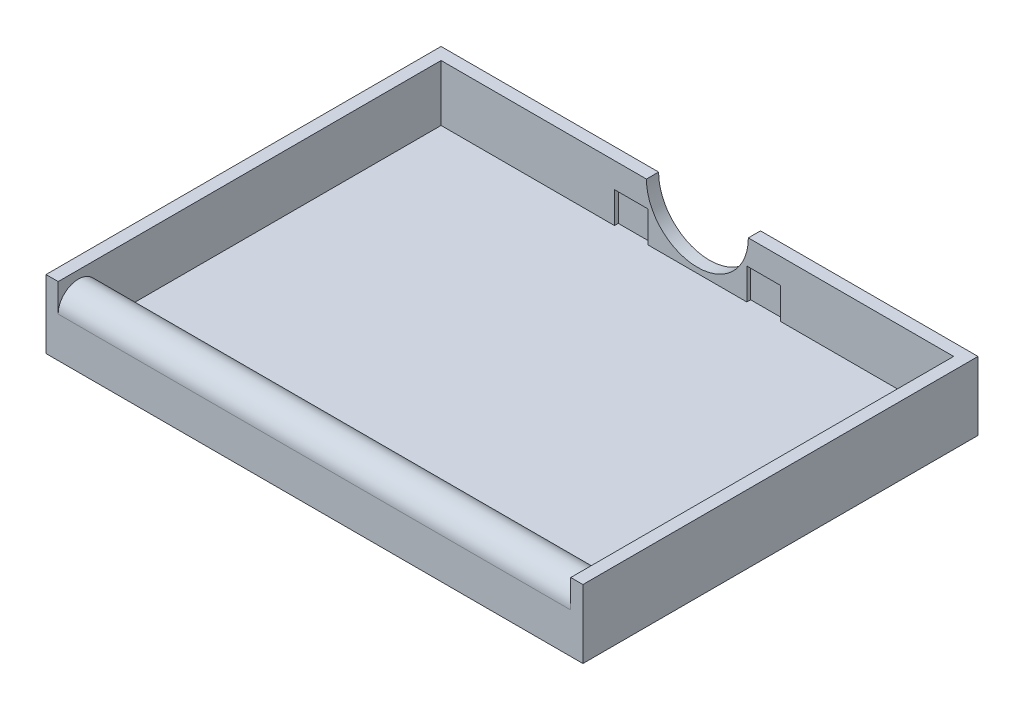
SolidWorks part; units mm, degrees
ref_plane "Front Plane" through (0, 0, 0) normal (0, 0, 1) x (1, 0, 0)
ref_plane "Top Plane" through (0, 0, 0) normal (0, 1, 0) x (1, 0, 0)
ref_plane "Right Plane" through (0, 0, 0) normal (1, 0, 0) x (0, 0, -1)
sketch "Sketch1" plane through (0, 0, 0) normal (0, 1, 0) x (1, 0, 0)
  line L1 (0, 0) -> (70.4, 0)
  line L2 (0, 0) -> (0, -50.7)
  line L3 (0, -50.7) -> (70.4, -50.7)
  line L4 (70.4, 0) -> (70.4, -50.7)
  dimension "D1" = 50.7
  dimension "D2" = 70.4
extrude "Boss-Extrude1" add sketch "Sketch1" along normal blind 1.6
sketch "Sketch2" plane through (0, 1.6, 0) normal (0, 1, 0) x (1, 0, 0)
  line L0 (70.4, -50.7) -> (70.4, 0) construction
  line L1 (0, -50.7) -> (70.4, -50.7)
  line L2 (0, -50.7) -> (0, -48.4)
  line L3 (0, -48.4) -> (70.4, -48.4)
  line L4 (70.4, -50.7) -> (70.4, -48.4)
  dimension "D1" = 2.3
extrude "Boss-Extrude2" add sketch "Sketch2" along normal blind 3.3
sketch "Sketch4" plane through (0, 0, 0) normal (-1, 0, 0) x (0, 0, 1)
  circle A0 centre (48.4, 4.9) radius 2.3
  dimension "D1" = 4.6
extrude "Boss-Extrude3" add sketch "Sketch4" against normal blind 70.4
sketch "Sketch5" plane through (0, 1.6, 0) normal (0, 1, 0) x (1, 0, 0)
  line L0 (70.4, 0) -> (0, 0) construction
  line L1 (1.6, -1.6) -> (68.8, -1.6)
  line L2 (1.6, -1.6) -> (1.6, -50.7)
  line L4 (68.8, -1.6) -> (68.8, -50.7)
  line L5 (0, 0) -> (0, -48.4) construction
  line L6 (70.4, -48.4) -> (70.4, 0) construction
  line L7 (68.8, -50.7) -> (70.4, -50.7)
  line L8 (0, -50.7) -> (1.6, -50.7)
  line L9 (0, -50.7) -> (0, 0)
  line L10 (0, 0) -> (70.4, 0)
  line L11 (70.4, -50.7) -> (70.4, 0)
  dimension "D1" = 1.6
  dimension "D2" = 1.6
  dimension "D3" = 1.6
extrude "Boss-Extrude4" add sketch "Sketch5" along normal blind 6.6
sketch "Sketch6" plane through (0, 0, 1.6) normal (0, 0, 1) x (1, 0, 0)
  line L0 (1.6, 8.2) -> (68.8, 8.2) construction
  circle A0 centre (35.2, 8.2) radius 6.7
  dimension "D1" = 13.4
extrude "Cut-Extrude1" cut sketch "Sketch6" against normal blind 6.6
sketch "Sketch7" plane through (0, 0, 1.6) normal (0, 0, 1) x (1, 0, 0)
  line L0 (28.5, 8.2) -> (28.5, 1.6)
  line L1 (1.6, 8.2) -> (28.5, 8.2) construction
  line L2 (1.6, 1.6) -> (34.0467, 1.6) construction
  line L3 (41.9, 8.2) -> (41.9, 1.6)
  line L4 (36.3533, 1.6) -> (68.8, 1.6) construction
  line L6 (28.5, 4.9) -> (24.4, 4.9)
  line L7 (28.5, 4.9) -> (28.5, 1.6)
  line L8 (28.5, 1.6) -> (24.4, 1.6)
  line L9 (24.4, 4.9) -> (24.4, 1.6)
  line L10 (41.9, 4.9) -> (46, 4.9)
  line L11 (41.9, 4.9) -> (41.9, 1.6)
  line L12 (41.9, 1.6) -> (46, 1.6)
  line L13 (46, 4.9) -> (46, 1.6)
  arc A0 (28.5, 8.2) -> (34.0467, 1.6) centre (35.2, 8.2) ccw construction
  line M3 (1.6, 1.6) -> (34.0467, 1.6)
  dimension "D1" = 4.1
  dimension "D2" = 4.1
extrude "Cut-Extrude2" cut sketch "Sketch7" against normal blind 0.5 contours L13 L10 L3 L12 | L6 L9 L0 M3
sketch "Sketch9" plane through (0, 0, 0) normal (0, -1, 0) x (1, 0, 0)
  line L4 (0, 50.7) -> (0, 0)
  line L5 (0, 0) -> (70.4, 0)
  line L6 (70.4, 0) -> (70.4, 50.7)
  line L7 (70.4, 50.7) -> (0, 50.7)
  line L8 (0, 50.7) -> (0, 0)
  line L9 (0, 0) -> (70.4, 0)
  line L10 (70.4, 0) -> (70.4, 50.7)
  line L11 (70.4, 50.7) -> (0, 50.7)
  dimension "D1" = 0
extrude "Boss-Extrude5" add sketch "Sketch9" along normal blind 0.8
sketch "Sketch10" plane through (0, 1.6, 0) normal (0, 1, 0) x (1, 0, 0)
  line L13 (24.4, -1.6) -> (1.6, -1.6)
  line L14 (1.6, -1.6) -> (1.6, -48.4)
  line L15 (1.6, -48.4) -> (68.8, -48.4)
  line L16 (68.8, -48.4) -> (68.8, -1.6)
  line L17 (68.8, -1.6) -> (46, -1.6)
  line L18 (46, -1.6) -> (46, -1.1)
  line L19 (46, -1.1) -> (41.9, -1.1)
  line L20 (41.9, -1.1) -> (41.9, -1.6)
  line L21 (41.9, -1.6) -> (36.3533, -1.6)
  line L22 (34.0467, -1.6) -> (28.5, -1.6)
  line L23 (28.5, -1.6) -> (28.5, -1.1)
  line L24 (28.5, -1.1) -> (24.4, -1.1)
  line L25 (24.4, -1.1) -> (24.4, -1.6)
  line L26 (24.4, -1.6) -> (1.6, -1.6)
  line L27 (1.6, -1.6) -> (1.6, -48.4)
  line L28 (1.6, -48.4) -> (68.8, -48.4)
  line L29 (68.8, -48.4) -> (68.8, -1.6)
  line L30 (68.8, -1.6) -> (46, -1.6)
  line L31 (46, -1.6) -> (46, -1.1)
  line L32 (46, -1.1) -> (41.9, -1.1)
  line L33 (41.9, -1.1) -> (41.9, -1.6)
  line L34 (41.9, -1.6) -> (36.3533, -1.6)
  line L35 (34.0467, -1.6) -> (28.5, -1.6)
  line L36 (28.5, -1.6) -> (28.5, -1.1)
  line L37 (28.5, -1.1) -> (24.4, -1.1)
  line L38 (24.4, -1.1) -> (24.4, -1.6)
  line L40 (36.3533, -1.6) -> (34.0467, -1.6)
  line L41 (36.3533, -1.6) -> (34.0467, -1.6)
  dimension "D1" = 0
extrude "Cut-Extrude3" cut sketch "Sketch10" against normal blind 0.8
sketch "Sketch11" plane through (0, 0, 0) normal (0, 0, -1) x (-1, 0, 0)
  line L5 (0, 8.2) -> (-28.5, 8.2)
  line L6 (-41.9, 8.2) -> (-70.4, 8.2)
  line L7 (-70.4, 8.2) -> (-70.4, -0.8)
  line L8 (-70.4, -0.8) -> (0, -0.8)
  line L9 (0, -0.8) -> (0, 8.2)
  line L10 (0, 8.2) -> (-28.5, 8.2)
  line L11 (-41.9, 8.2) -> (-70.4, 8.2)
  line L12 (-70.4, 8.2) -> (-70.4, -0.8)
  line L13 (-70.4, -0.8) -> (0, -0.8)
  line L14 (0, -0.8) -> (0, 8.2)
  arc A1 (-41.9, 8.2) -> (-28.5, 8.2) centre (-35.2, 8.2) ccw
  arc A2 (-41.9, 8.2) -> (-28.5, 8.2) centre (-35.2, 8.2) ccw
  dimension "D1" = 0
extrude "Boss-Extrude6" add sketch "Sketch11" along normal blind 0.2
sketch "Sketch12" plane through (0, 0, 1.6) normal (0, 0, 1) x (1, 0, 0)
  line L13 (28.5, 4.9) -> (28.5, 0.8)
  line L14 (28.5, 0.8) -> (41.9, 0.8)
  line L15 (41.9, 0.8) -> (41.9, 4.9)
  line L16 (41.9, 4.9) -> (46, 4.9)
  line L17 (46, 4.9) -> (46, 0.8)
  line L18 (46, 0.8) -> (68.8, 0.8)
  line L19 (68.8, 0.8) -> (68.8, 8.2)
  line L20 (68.8, 8.2) -> (41.9, 8.2)
  line L21 (28.5, 8.2) -> (1.6, 8.2)
  line L22 (1.6, 8.2) -> (1.6, 0.8)
  line L23 (1.6, 0.8) -> (24.4, 0.8)
  line L24 (24.4, 0.8) -> (24.4, 4.9)
  line L25 (24.4, 4.9) -> (28.5, 4.9)
  line L26 (28.5, 4.9) -> (28.5, 0.8)
  line L27 (28.5, 0.8) -> (41.9, 0.8)
  line L28 (41.9, 0.8) -> (41.9, 4.9)
  line L29 (41.9, 4.9) -> (46, 4.9)
  line L30 (46, 4.9) -> (46, 0.8)
  line L31 (46, 0.8) -> (68.8, 0.8)
  line L32 (68.8, 0.8) -> (68.8, 8.2)
  line L33 (68.8, 8.2) -> (41.9, 8.2)
  line L34 (28.5, 8.2) -> (1.6, 8.2)
  line L35 (1.6, 8.2) -> (1.6, 0.8)
  line L36 (1.6, 0.8) -> (24.4, 0.8)
  line L37 (24.4, 0.8) -> (24.4, 4.9)
  line L38 (24.4, 4.9) -> (28.5, 4.9)
  arc A1 (28.5, 8.2) -> (41.9, 8.2) centre (35.2, 8.2) ccw
  arc A2 (28.5, 8.2) -> (41.9, 8.2) centre (35.2, 8.2) ccw
  dimension "D1" = 0
extrude "Cut-Extrude4" cut sketch "Sketch12" against normal blind 0.2
sketch "Sketch13" plane through (0, 0, 1.1) normal (0, 0, 1) x (1, 0, 0)
  line L0 (46, 0.8) -> (46, 4.9) construction
  line L1 (46, 4.9) -> (41.9, 4.9) construction
  line L2 (41.9, 4.9) -> (41.9, 0.8) construction
  line L3 (41.9, 0.8) -> (46, 0.8) construction
  line L4 (28.5, 4.9) -> (24.4, 4.9) construction
  line L5 (24.4, 4.9) -> (24.4, 0.8) construction
  line L6 (24.4, 0.8) -> (28.5, 0.8) construction
  line L7 (28.5, 0.8) -> (28.5, 4.9) construction
  line L8 (46, 0.8) -> (46, 4.9)
  line L9 (46, 4.9) -> (41.9, 4.9)
  line L10 (41.9, 4.9) -> (41.9, 0.8)
  line L11 (41.9, 0.8) -> (46, 0.8)
  line L12 (28.5, 4.9) -> (24.4, 4.9)
  line L13 (24.4, 4.9) -> (24.4, 0.8)
  line L14 (24.4, 0.8) -> (28.5, 0.8)
  line L15 (28.5, 0.8) -> (28.5, 4.9)
extrude "Cut-Extrude5" cut sketch "Sketch13" against normal blind 0.2
sketch "Sketch14" plane through (0, 0, 0) normal (-1, 0, 0) x (0, 0, 1)
  line L4 (50.7, 8.2) -> (-0.2, 8.2)
  line L5 (-0.2, 8.2) -> (-0.2, -0.8)
  line L6 (-0.2, -0.8) -> (50.7, -0.8)
  line L7 (50.7, -0.8) -> (50.7, 8.2)
  line L8 (50.7, 8.2) -> (-0.2, 8.2)
  line L9 (-0.2, 8.2) -> (-0.2, -0.8)
  line L10 (-0.2, -0.8) -> (50.7, -0.8)
  line L11 (50.7, -0.8) -> (50.7, 8.2)
  dimension "D1" = 0
extrude "Boss-Extrude7" add sketch "Sketch14" along normal blind 0.1
sketch "Sketch15" plane through (1.6, 0, 0) normal (1, 0, 0) x (0, 0, -1)
  line L5 (-48.4, 2.6) -> (-48.4, 0.8)
  line L6 (-48.4, 0.8) -> (-1.4, 0.8)
  line L7 (-1.4, 0.8) -> (-1.4, 8.2)
  line L8 (-1.4, 8.2) -> (-50.7, 8.2)
  line L9 (-50.7, 8.2) -> (-50.7, 4.9)
  line L10 (-48.4, 2.6) -> (-48.4, 0.8)
  line L11 (-48.4, 0.8) -> (-1.4, 0.8)
  line L12 (-1.4, 0.8) -> (-1.4, 8.2)
  line L13 (-1.4, 8.2) -> (-50.7, 8.2)
  line L14 (-50.7, 8.2) -> (-50.7, 4.9)
  arc A1 (-48.4, 2.6) -> (-50.7, 4.9) centre (-48.4, 4.9) ccw
  arc A2 (-48.4, 2.6) -> (-50.7, 4.9) centre (-48.4, 4.9) ccw
  dimension "D1" = 0
extrude "Cut-Extrude6" cut sketch "Sketch15" against normal blind 0.1
sketch "Sketch16" plane through (68.8, 0, 0) normal (-1, 0, 0) x (0, 0, 1)
  line L5 (50.7, 8.2) -> (1.4, 8.2)
  line L6 (1.4, 8.2) -> (1.4, 0.8)
  line L7 (1.4, 0.8) -> (48.4, 0.8)
  line L8 (48.4, 0.8) -> (48.4, 2.6)
  line L9 (50.7, 4.9) -> (50.7, 8.2)
  line L10 (50.7, 8.2) -> (1.4, 8.2)
  line L11 (1.4, 8.2) -> (1.4, 0.8)
  line L12 (1.4, 0.8) -> (48.4, 0.8)
  line L13 (48.4, 0.8) -> (48.4, 2.6)
  line L14 (50.7, 4.9) -> (50.7, 8.2)
  arc A1 (50.7, 4.9) -> (48.4, 2.6) centre (48.4, 4.9) ccw
  arc A2 (50.7, 4.9) -> (48.4, 2.6) centre (48.4, 4.9) ccw
  dimension "D1" = 0
extrude "Cut-Extrude7" cut sketch "Sketch16" against normal blind 0.1
sketch "Sketch17" plane through (70.4, 0, 0) normal (1, 0, 0) x (0, 0, -1)
  line L4 (-50.7, 8.2) -> (-50.7, -0.8)
  line L5 (-50.7, -0.8) -> (0.2, -0.8)
  line L6 (0.2, -0.8) -> (0.2, 8.2)
  line L7 (0.2, 8.2) -> (-50.7, 8.2)
  line L8 (-50.7, 8.2) -> (-50.7, -0.8)
  line L9 (-50.7, -0.8) -> (0.2, -0.8)
  line L10 (0.2, -0.8) -> (0.2, 8.2)
  line L11 (0.2, 8.2) -> (-50.7, 8.2)
  dimension "D1" = 0
extrude "Boss-Extrude8" add sketch "Sketch17" along normal blind 0.1
sketch "Sketch18" plane through (41.9, 0, 0) normal (1, 0, 0) x (0, 0, -1)
  line L4 (-1.4, 4.9) -> (-1.4, 0.8)
  line L5 (-1.4, 0.8) -> (-0.9, 0.8)
  line L6 (-0.9, 0.8) -> (-0.9, 4.9)
  line L7 (-0.9, 4.9) -> (-1.4, 4.9)
  line L8 (-1.4, 4.9) -> (-1.4, 0.8)
  line L9 (-1.4, 0.8) -> (-0.9, 0.8)
  line L10 (-0.9, 0.8) -> (-0.9, 4.9)
  line L11 (-0.9, 4.9) -> (-1.4, 4.9)
  dimension "D1" = 0
extrude "Cut-Extrude8" cut sketch "Sketch18" against normal blind 0.2
sketch "Sketch19" plane through (28.5, 0, 0) normal (-1, 0, 0) x (0, 0, 1)
  line L4 (0.9, 0.8) -> (1.4, 0.8)
  line L5 (1.4, 0.8) -> (1.4, 4.9)
  line L6 (1.4, 4.9) -> (0.9, 4.9)
  line L7 (0.9, 4.9) -> (0.9, 0.8)
  line L8 (0.9, 0.8) -> (1.4, 0.8)
  line L9 (1.4, 0.8) -> (1.4, 4.9)
  line L10 (1.4, 4.9) -> (0.9, 4.9)
  line L11 (0.9, 4.9) -> (0.9, 0.8)
  dimension "D1" = 0
extrude "Cut-Extrude9" cut sketch "Sketch19" against normal blind 0.2
sketch "Sketch21" plane through (46, 0, 0) normal (-1, 0, 0) x (0, 0, 1)
  line L4 (0.9, 0.8) -> (1.4, 0.8)
  line L5 (1.4, 0.8) -> (1.4, 4.9)
  line L6 (1.4, 4.9) -> (0.9, 4.9)
  line L7 (0.9, 4.9) -> (0.9, 0.8)
  line L8 (0.9, 0.8) -> (1.4, 0.8)
  line L9 (1.4, 0.8) -> (1.4, 4.9)
  line L10 (1.4, 4.9) -> (0.9, 4.9)
  line L11 (0.9, 4.9) -> (0.9, 0.8)
  dimension "D1" = 0
extrude "Cut-Extrude10" cut sketch "Sketch21" against normal blind 0.1
sketch "Sketch22" plane through (24.4, 0, 0) normal (1, 0, 0) x (0, 0, -1)
  line L4 (-1.4, 4.9) -> (-1.4, 0.8)
  line L5 (-1.4, 0.8) -> (-0.9, 0.8)
  line L6 (-0.9, 0.8) -> (-0.9, 4.9)
  line L7 (-0.9, 4.9) -> (-1.4, 4.9)
  line L8 (-1.4, 4.9) -> (-1.4, 0.8)
  line L9 (-1.4, 0.8) -> (-0.9, 0.8)
  line L10 (-0.9, 0.8) -> (-0.9, 4.9)
  line L11 (-0.9, 4.9) -> (-1.4, 4.9)
  dimension "D1" = 0
extrude "Cut-Extrude11" cut sketch "Sketch22" against normal blind 0.1
sketch "Sketch24" plane through (0, 0.8, 0) normal (0, 1, 0) x (1, 0, 0)
  line L0 (1.5, -1.4) -> (1.5, -50.7) construction
  line L1 (1.5, -37.9866) -> (68.9, -37.9866)
  line L2 (1.5, -37.9866) -> (1.5, -53.4732)
  line L3 (1.5, -53.4732) -> (68.9, -53.4732)
  line L4 (68.9, -37.9866) -> (68.9, -53.4732)
extrude "Cut-Extrude12" cut sketch "Sketch24" along normal blind 23.1
sketch "Sketch25" plane through (0, 0.8, 0) normal (0, 1, 0) x (1, 0, 0)
  line L0 (68.9, -50.7) -> (68.9, -1.4) construction
  line L1 (1.5, -50.7) -> (68.9, -50.7)
  line L2 (1.5, -50.7) -> (1.5, -49.1)
  line L3 (1.5, -49.1) -> (68.9, -49.1)
  line L4 (68.9, -50.7) -> (68.9, -49.1)
  line L5 (1.5, -1.4) -> (24.3, -1.4) construction
  dimension "D1" = 47.7
extrude "Boss-Extrude9" add sketch "Sketch25" along normal blind 3.7
sketch "Sketch26" plane through (1.5, 0, 0) normal (1, 0, 0) x (0, 0, -1)
  line L0 (-50.7, 8.2) -> (-50.7, -0.8) construction
  line L1 (-50.7, -0.8) -> (0.2, -0.8) construction
  circle A0 centre (-49.1, 4.5) radius 2.65
  dimension "D1" = 5.3
extrude "Boss-Extrude10" add sketch "Sketch26" along normal blind 67.7
sketch "Sketch27" plane through (0, 0, 50.7) normal (0, 0, 1) x (1, 0, 0)
  line L0 (68.9, 8.2) -> (70.5, 8.2) construction
  line L1 (70.5, -0.8) -> (68.9, -0.8)
  line L2 (70.5, -0.8) -> (70.5, 8.2)
  line L3 (70.5, 8.2) -> (68.9, 8.2)
  line L4 (68.9, 4.5) -> (68.9, 8.2)
  line L5 (68.9, 6.6125) -> (68.9, 8.2) construction
  line L7 (-0.1, -0.8) -> (1.5, -0.8)
  line L8 (-0.1, -0.8) -> (-0.1, 8.2)
  line L9 (-0.1, 8.2) -> (1.5, 8.2)
  line L10 (1.5, 4.5) -> (1.5, 8.2)
  line L11 (68.9, 4.5) -> (1.5, 4.5)
  line L12 (70.5, 4.77) -> (70.5, -0.8)
  line L13 (70.5, -0.8) -> (-0.1, -0.8)
  line L14 (-0.1, 4.77) -> (-0.1, -0.8)
  line M6 (68.9, 6.6125) -> (69.2, 6.6125)
  line M7 (69.2, 6.6125) -> (69.2, 2.3875)
  line M8 (69.2, 2.3875) -> (1.5, 2.3875)
  line M9 (1.5, 2.3875) -> (1.5, 6.6125)
  line M10 (1.5, 6.6125) -> (1.5, 8.2)
  line M11 (1.5, 8.2) -> (-0.1, 8.2)
  line M12 (-0.1, 8.2) -> (-0.1, -0.8)
  line M13 (-0.1, -0.8) -> (70.5, -0.8)
  line M14 (70.5, -0.8) -> (70.5, 8.2)
  line M15 (70.5, 8.2) -> (68.9, 8.2)
  line M16 (68.9, 8.2) -> (68.9, 6.6125)
  dimension "D1" = 5.3
extrude "Boss-Extrude13" add sketch "Sketch27" along normal blind 1.05 contours L8 L2 M16 M6 M7 M8 M9 M10 M11 M12 M13 M14 M15 | L4 L11 M9 M8 M7 M6
